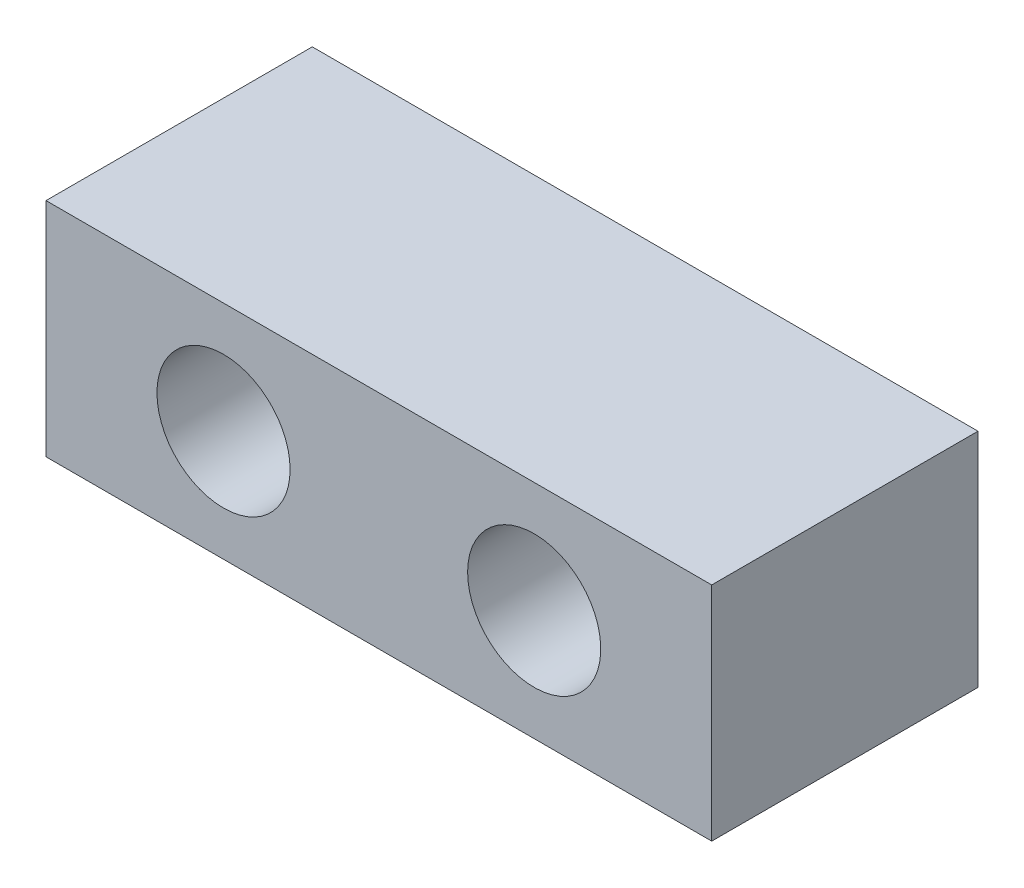
SolidWorks part; units mm, degrees
ref_plane "Plan de face" through (0, 0, 0) normal (0, 0, 1) x (1, 0, 0)
ref_plane "Plan de dessus" through (0, 0, 0) normal (0, 1, 0) x (1, 0, 0)
ref_plane "Plan de droite" through (0, 0, 0) normal (1, 0, 0) x (0, 0, -1)
sketch "Esquisse1" plane through (0, 0, 0) normal (0, 0, 1) x (1, 0, 0)
  line L1 (0, 0) -> (30, 0)
  line L2 (0, 0) -> (0, 10)
  line L3 (0, 10) -> (30, 10)
  line L4 (30, 0) -> (30, 10)
  dimension "D1" = 10
  dimension "D2" = 30
extrude "Boss.-Extru.1" add sketch "Esquisse1" along normal blind 12
sketch "Esquisse2" plane through (0, 0, 12) normal (0, 0, 1) x (1, 0, 0)
  line L0 (15, 0) -> (15, 10) construction
  line L1 (0, 0) -> (30, 0) construction
  line L2 (30, 10) -> (0, 10) construction
  line L3 (8, 5) -> (15, 5) construction
  circle A0 centre (8, 5) radius 3
  circle A1 centre (22, 5) radius 3
  dimension "D1" = 6
  dimension "D2" = 7
extrude "Enlèv. mat.-Extru.1" cut sketch "Esquisse2" against normal through all both and the other way through all
